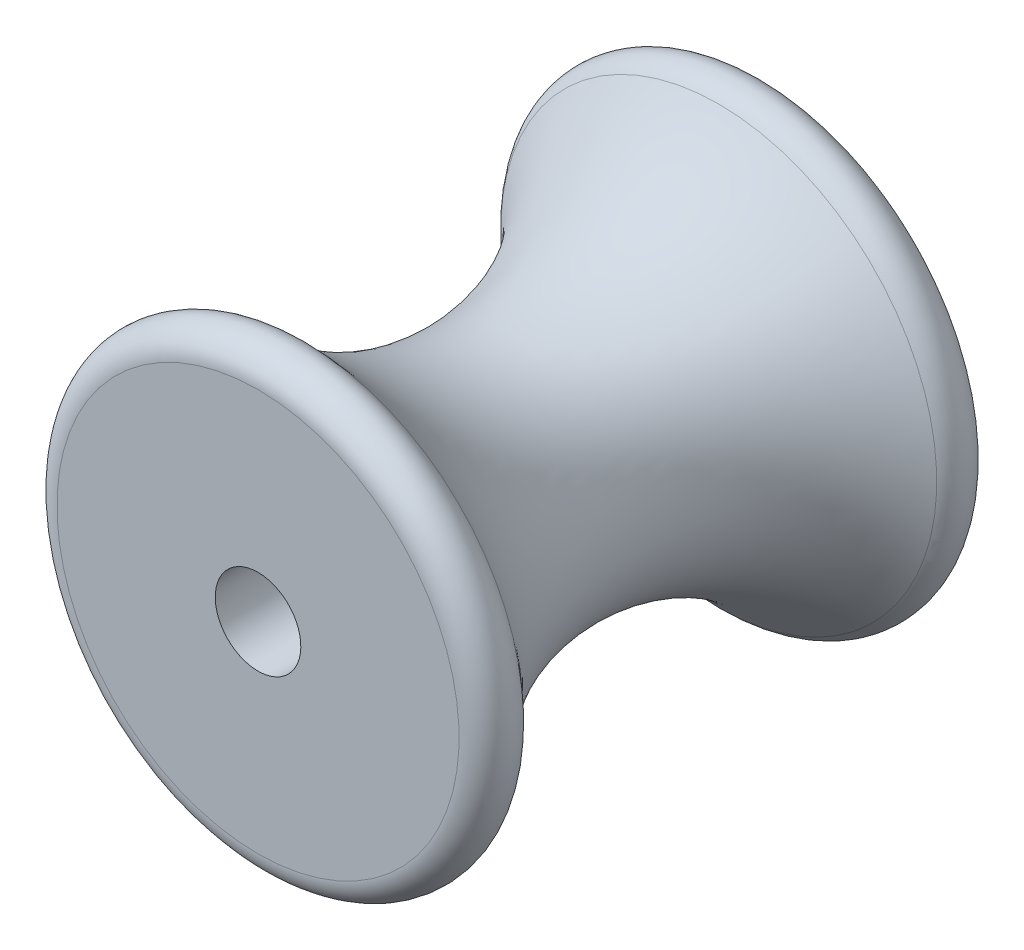
SolidWorks part; units mm, degrees
ref_plane "Front Plane" through (0, 0, 0) normal (0, 0, 1) x (1, 0, 0)
ref_plane "Top Plane" through (0, 0, 0) normal (0, 1, 0) x (1, 0, 0)
ref_plane "Right Plane" through (0, 0, 0) normal (1, 0, 0) x (0, 0, -1)
sketch "Sketch1" plane through (0, 0, 0) normal (1, 0, 0) x (0, 0, -1)
  line L0 (10, 0) -> (-10, 0) construction
  line L1 (10, 16.5) -> (10, -25.2654) construction
  line L2 (10, 1.6) -> (-10, 1.6) construction
  line L4 (0, 9.3697) -> (0, -9.3697) construction
  line L5 (10, 1.6) -> (10, 14.5) construction
  line L6 (-10, 1.6) -> (-10, 14.5) construction
  line L7 (9.5, 1.6) -> (9.5, 11.3775)
  line L8 (-9.5, 1.6) -> (-9.5, 11.3775)
  line L9 (9.5, 1.6) -> (-9.5, 1.6)
  circle A0 centre (0, 14.5) radius 10 construction
  arc A1 (9.5, 11.3775) -> (-9.5, 11.3775) centre (0, 14.5) cw
  point P2 (0, 0)
  dimension "D1" = 1
revolve "Revolve1" add sketch "Sketch1" angle 360 about L0
fillet "Fillet1" radius 1 2 edges at (0, 11.3775, 9.5) (0, 11.3775, -9.5)
